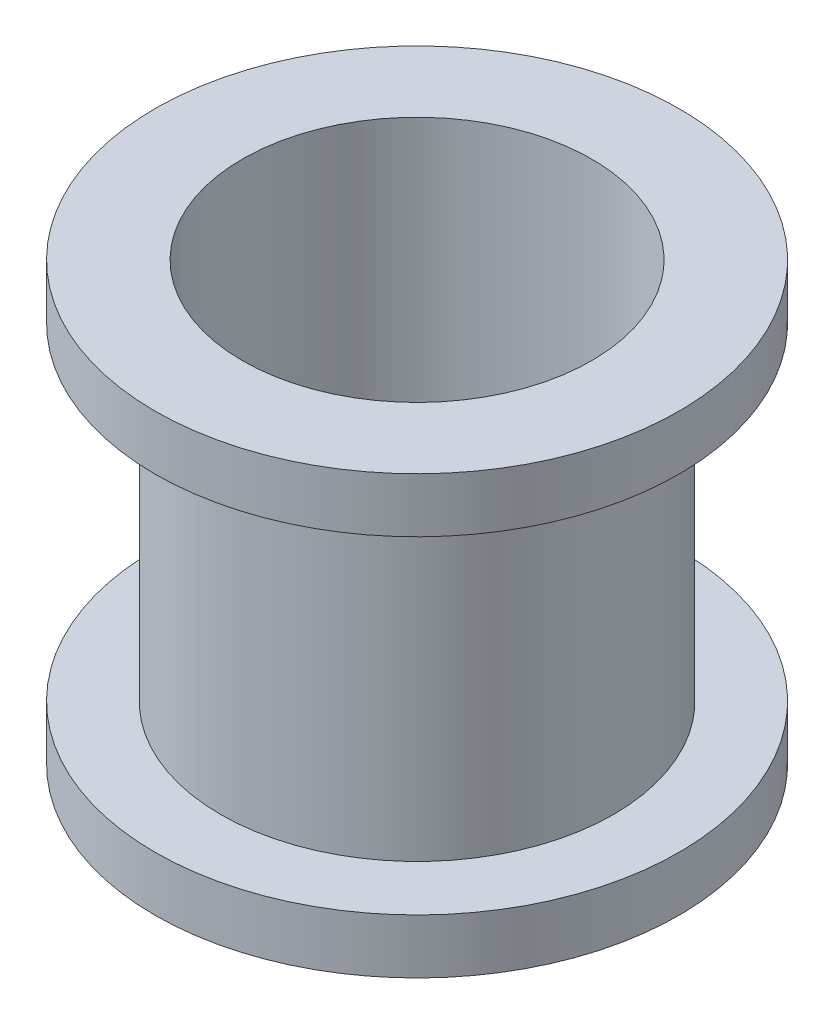
SolidWorks part; units mm, degrees
ref_plane "前视基准面" through (0, 0, 0) normal (0, 0, 1) x (1, 0, 0)
ref_plane "上视基准面" through (0, 0, 0) normal (0, 1, 0) x (1, 0, 0)
ref_plane "右视基准面" through (0, 0, 0) normal (1, 0, 0) x (0, 0, -1)
sketch "Sketch1" plane through (0, 0, 0) normal (0, 1, 0) x (1, 0, 0)
  circle A0 centre (0, 0) radius 18
  dimension "D1" = 36
extrude "Extrude1" add sketch "Sketch1" along normal mid plane 30
sketch "Sketch2" plane through (0, 15, 0) normal (0, 1, 0) x (1, 0, 0)
  circle A0 centre (0, 0) radius 24
  dimension "D1" = 48
extrude "Extrude2" add sketch "Sketch2" along normal blind 5
mirror "Mirror1" about plane through (0, 0, 0) normal (0, 1, 0) of "Extrude2"
sketch "Sketch3" plane through (0, 0, 0) normal (0, 1, 0) x (1, 0, 0)
  circle A0 centre (0, 0) radius 16
  dimension "D1" = 32
extrude "Extrude4" cut sketch "Sketch3" against normal through all both and the other way through all
ref_plane "Plane1" through (0, 0, 0) normal (0, 1, 0) x (1, 0, 0)
